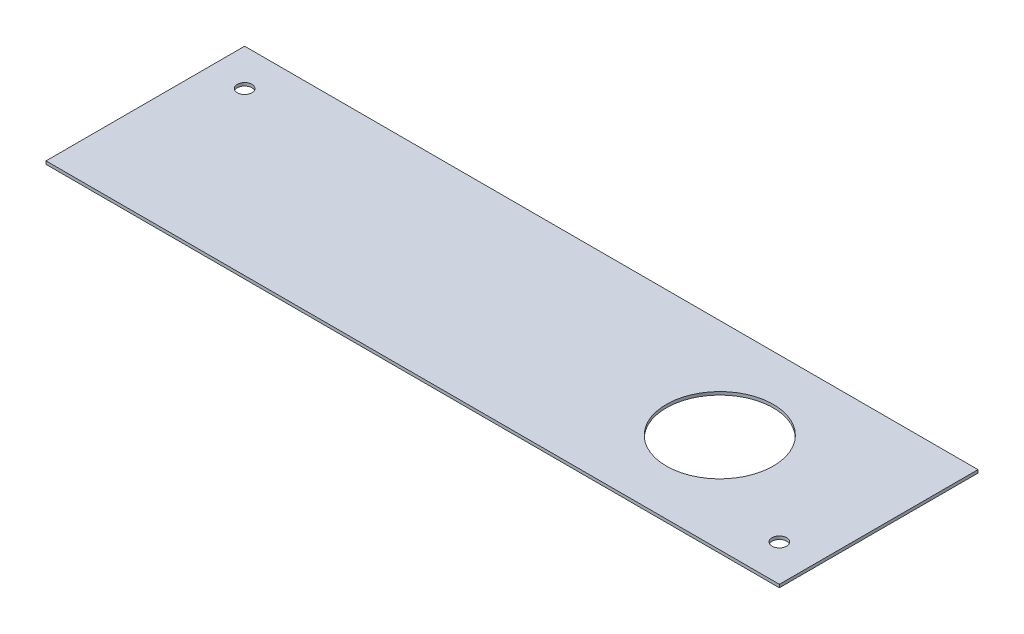
SolidWorks part; units mm, degrees
ref_plane "Front Plane" through (0, 0, 0) normal (0, 0, 1) x (1, 0, 0)
ref_plane "Top Plane" through (0, 0, 0) normal (0, 1, 0) x (1, 0, 0)
ref_plane "Right Plane" through (0, 0, 0) normal (1, 0, 0) x (0, 0, -1)
sketch "Sketch1" plane through (0, 0, 0) normal (0, 1, 0) x (1, 0, 0)
  line L1 (-172.1169, 24.7681) -> (67.8831, 24.7681)
  line L2 (-172.1169, 24.7681) -> (-172.1169, -40.2319)
  line L3 (-172.1169, -40.2319) -> (67.8831, -40.2319)
  line L4 (67.8831, 24.7681) -> (67.8831, -40.2319)
  dimension "D1" = 65
  dimension "D2" = 240
extrude "Boss-Extrude1" add sketch "Sketch1" along normal blind 1
hole_wizard "M4 Clearance Slot1" positions "Sketch2" profile "Sketch3" size "M4" standard "ANSI Metric" slot yes end condition through all
sketch "Sketch2" plane through (0, 1, 0) normal (0, 1, 0) x (1, 0, 0)
  line L0 (67.8831, 24.7681) -> (-172.1169, 24.7681) construction
  line L1 (-172.1169, 24.7681) -> (-172.1169, -40.2319) construction
  line L2 (67.8831, -40.2319) -> (67.8831, 24.7681) construction
  line L3 (-172.1169, -40.2319) -> (67.8831, -40.2319) construction
  point P0 (-160.1169, 12.7681)
  point P2 (55.8831, -28.2319)
  dimension "D1" = 12
  dimension "D2" = 12
  dimension "D3" = 12
  dimension "D4" = 12
sketch "Sketch3" plane through (-160.1169, 1, -12.7681) normal (1, 0, 0) x (0, 0, 1)
  line L0 (0, 0) -> (0, 1)
  line L1 (0, 1) -> (2.4, 1)
  line L2 (2.4, 1) -> (2.4, 0)
  line L5 (2.4, 0) -> (0, 0)
  line L11 (0, -6.35) -> (0, 107.95) construction
  dimension "Thru Hole Dia." = 4.8
  dimension "Thru Hole Depth" = 1
sketch "Sketch4" plane through (0, 1, 0) normal (0, 1, 0) x (1, 0, 0)
  line L0 (67.8831, 24.7681) -> (-172.1169, 24.7681) construction
  line L1 (-172.1169, 24.7681) -> (-172.1169, -40.2319) construction
  circle A0 centre (15.8831, -7.7319) radius 17.5
  dimension "D3" = 35
  dimension "D1" = 32.5
  dimension "D2" = 188
extrude "Cut-Extrude1" cut sketch "Sketch4" against normal blind 5
